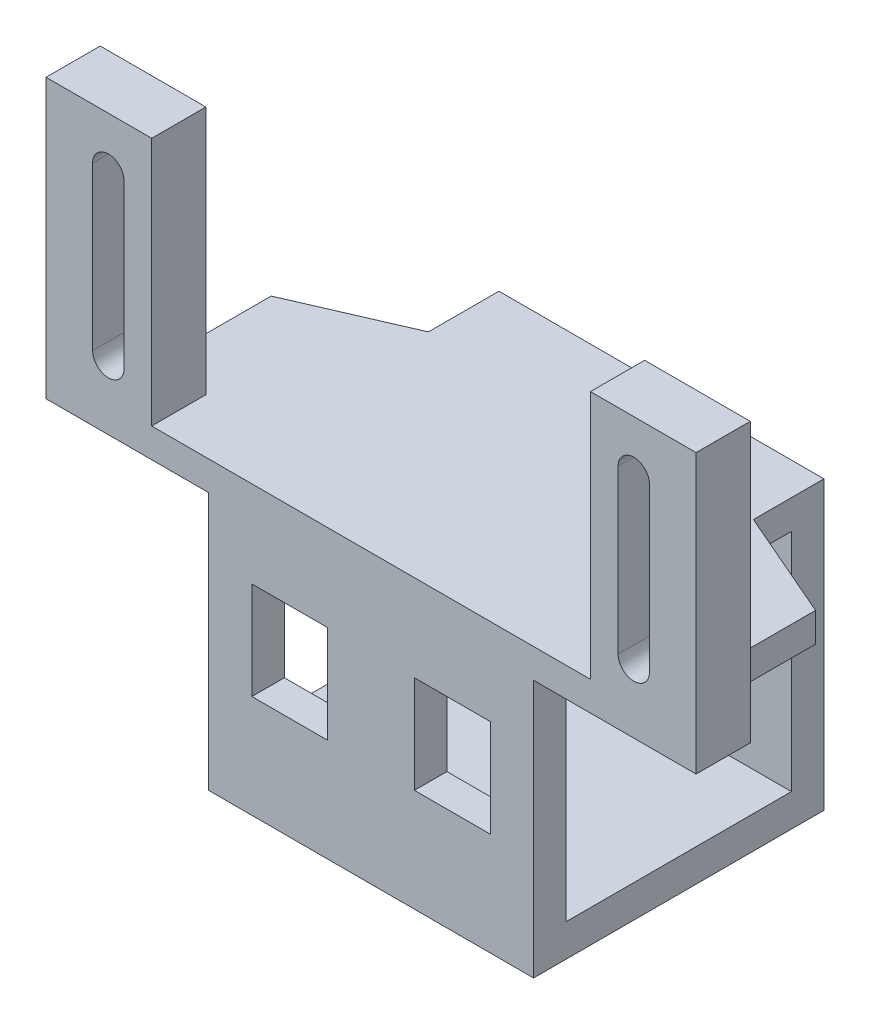
SolidWorks part; units mm, degrees
ref_plane "前视基准面" through (0, 0, 0) normal (0, 0, 1) x (1, 0, 0)
ref_plane "上视基准面" through (0, 0, 0) normal (0, 1, 0) x (1, 0, 0)
ref_plane "右视基准面" through (0, 0, 0) normal (1, 0, 0) x (0, 0, -1)
other "Configuration Table"
sketch "草图1" plane through (0, 0, 0) normal (1, 0, 0) x (0, 0, -1)
  line L0 (-3, 25) -> (23.8, 25)
  line L5 (0, 0) -> (20.8, 0)
  line L6 (0, 0) -> (0, 22)
  line L7 (0, 22) -> (20.8, 22)
  line L8 (20.8, 0) -> (20.8, 22)
  line L9 (23.8, -3) -> (23.8, 25)
  line L10 (-3, -3) -> (23.8, -3)
  line L11 (-3, -3) -> (-3, 25)
  point P0 (0, 0)
  dimension "D1" = 22
  dimension "D2" = 20.8
  dimension "D3" = 3
extrude "凸台-拉伸1" add sketch "草图1" along normal blind 30
sketch "草图2" plane through (0, 0, -23.8) normal (0, 0, -1) x (-1, 0, 0)
  line L0 (-30, 11) -> (4.4684, 11) construction
  line L1 (-30, -3) -> (-30, 25) construction
  line L2 (0, -3) -> (0, 25) construction
  line L3 (-24, 8.5) -> (-21, 8.5)
  line L4 (-24, 8.5) -> (-24, 13.5)
  line L5 (-24, 13.5) -> (-21, 13.5)
  line L6 (-21, 8.5) -> (-21, 13.5)
  line L7 (-24, 8.5) -> (-21, 13.5) construction
  line L8 (-24, 13.5) -> (-21, 8.5) construction
  line L9 (-9, 8.5) -> (-6, 8.5)
  line L10 (-9, 8.5) -> (-9, 13.5)
  line L11 (-9, 13.5) -> (-6, 13.5)
  line L12 (-6, 8.5) -> (-6, 13.5)
  line L13 (-9, 8.5) -> (-6, 13.5) construction
  line L14 (-9, 13.5) -> (-6, 8.5) construction
  point P4 (-22.5, 11)
  point P9 (-7.5, 11)
  dimension "D1" = 3
  dimension "D2" = 5
  dimension "D3" = 6
  dimension "D4" = 3
  dimension "D5" = 6
extrude "切除-拉伸1" cut sketch "草图2" against normal blind 30
sketch "草图3" plane through (0, 0, 0) normal (-1, 0, 0) x (0, 0, 1)
  line L0 (0, 22) -> (0, 0) construction
  line L1 (-20.8, 22) -> (0, 22)
  line L2 (-20.8, 22) -> (-20.8, 20.8)
  line L3 (-20.8, 20.8) -> (0, 20.8)
  line L4 (0, 22) -> (0, 20.8)
  dimension "D1" = 1.2
extrude "凸台-拉伸2" add sketch "草图3" against normal blind 30
sketch "草图4" plane through (0, 0, 0) normal (-1, 0, 0) x (0, 0, 1)
  line L1 (-23.8, 25) -> (3.1629, 25)
  line L2 (-23.8, 25) -> (-23.8, 23.5)
  line L3 (-23.8, 23.5) -> (3.1629, 23.5)
  line L4 (3.1629, 25) -> (3.1629, 23.5)
  dimension "D1" = 1.5
extrude "切除-拉伸2" cut sketch "草图4" against normal blind 30
sketch "草图5" plane through (0, 0, -23.8) normal (0, 0, -1) x (-1, 0, 0)
  line L0 (-21, 13.5) -> (-24, 13.5) construction
  line L1 (-21, 13.5) -> (-24, 13.5)
  line L2 (-24, 13.5) -> (-24, 8.5) construction
  line L3 (-24, 13.5) -> (-24, 8.5)
  line L4 (-9, 8.5) -> (-6, 8.5) construction
  line L5 (-6, 8.5) -> (-6, 13.5) construction
  line L6 (-9, 13.5) -> (-9, 8.5) construction
  line L7 (-6, 13.5) -> (-9, 13.5) construction
  line L8 (-21, 8.5) -> (-21, 13.5) construction
  line L9 (-24, 8.5) -> (-21, 8.5) construction
  line L10 (-9, 8.5) -> (-6, 8.5)
  line L11 (-6, 8.5) -> (-6, 13.5)
  line L12 (-9, 13.5) -> (-9, 8.5)
  line L13 (-6, 13.5) -> (-9, 13.5)
  line L14 (-21, 8.5) -> (-21, 13.5)
  line L15 (-24, 8.5) -> (-21, 8.5)
  line L16 (-19, 15.5) -> (-26, 15.5)
  line L17 (-26, 15.5) -> (-26, 6.5)
  line L18 (-26, 6.5) -> (-19, 6.5)
  line L19 (-19, 6.5) -> (-19, 15.5)
  line L20 (-11, 15.5) -> (-11, 6.5)
  line L21 (-11, 6.5) -> (-4, 6.5)
  line L22 (-4, 6.5) -> (-4, 15.5)
  line L23 (-4, 15.5) -> (-11, 15.5)
  dimension "D1" = 2
extrude "切除-拉伸3" cut sketch "草图5" against normal through all
sketch "草图6" plane through (0, 0, 3) normal (0, 0, 1) x (1, 0, 0)
  line L0 (15, 23.2563) -> (15, 13.0712) construction
  line L1 (0, 23.5) -> (0, -3) construction
  line L2 (30, 23.5) -> (30, -3) construction
  line L4 (45, 20.8) -> (45, 46.5)
  line L5 (45, 46.5) -> (35.25, 46.5)
  line L6 (-15, 20.8) -> (-15, 46.5)
  line L7 (-15, 20.8) -> (45, 20.8)
  line L8 (30, 20.8) -> (0, 20.8) construction
  line L9 (30, 23.5) -> (0, 23.5) construction
  line L11 (-5.25, 46.5) -> (-15, 46.5)
  line L13 (-5.25, 23.5) -> (-5.25, 46.5)
  line L16 (35.25, 23.5) -> (-5.25, 23.5)
  line L17 (35.25, 23.5) -> (35.25, 46.5)
  line L19 (-9.25, 41.8) -> (-9.25, 26.8) construction
  line L20 (-7.8, 41.8) -> (-7.8, 26.8)
  line L21 (-10.7, 41.8) -> (-10.7, 26.8)
  line L22 (39.25, 41.8) -> (39.25, 26.8) construction
  line L23 (37.8, 41.8) -> (37.8, 26.8)
  line L24 (40.7, 41.8) -> (40.7, 26.8)
  arc A0 (-7.8, 41.8) -> (-10.7, 41.8) centre (-9.25, 41.8) ccw
  arc A1 (-10.7, 26.8) -> (-7.8, 26.8) centre (-9.25, 26.8) ccw
  arc A2 (37.8, 41.8) -> (40.7, 41.8) centre (39.25, 41.8) cw
  arc A3 (40.7, 26.8) -> (37.8, 26.8) centre (39.25, 26.8) cw
  point P1 (15, 31.3508)
  point P6 (15, 36.4987)
  point P17 (-9.25, 34.3)
  point P32 (39.25, 34.3)
  dimension "D1" = 30
  dimension "D2" = 23
  dimension "D3" = 9.75
  dimension "D4" = 5.25
  dimension "D5" = 35.25
  dimension "D6" = 9.75
  dimension "D7" = 4
  dimension "D8" = 2.9
  dimension "D9" = 15
  dimension "D10" = 6
extrude "凸台-拉伸3" add sketch "草图6" against normal blind 5
sketch "草图7" plane through (0, 23.5, 0) normal (0, 1, 0) x (1, 0, 0)
  line L0 (-10.125, 2) -> (-10.125, 12.9)
  line L1 (-5.25, 2) -> (-15, 2) construction
  line L2 (-10.125, 12.9) -> (15, 23.8)
  line L3 (30, 23.8) -> (0, 23.8) construction
  line L4 (15, 23.8) -> (40.125, 12.9)
  line L5 (40.125, 12.9) -> (40.125, 2)
  line L6 (45, 2) -> (35.25, 2) construction
  line L7 (40.125, 2) -> (-10.125, 2)
extrude "凸台-拉伸4" add sketch "草图7" against normal up to surface (2.7 mm away) up to face at (15, 20.8, -3.1333)
